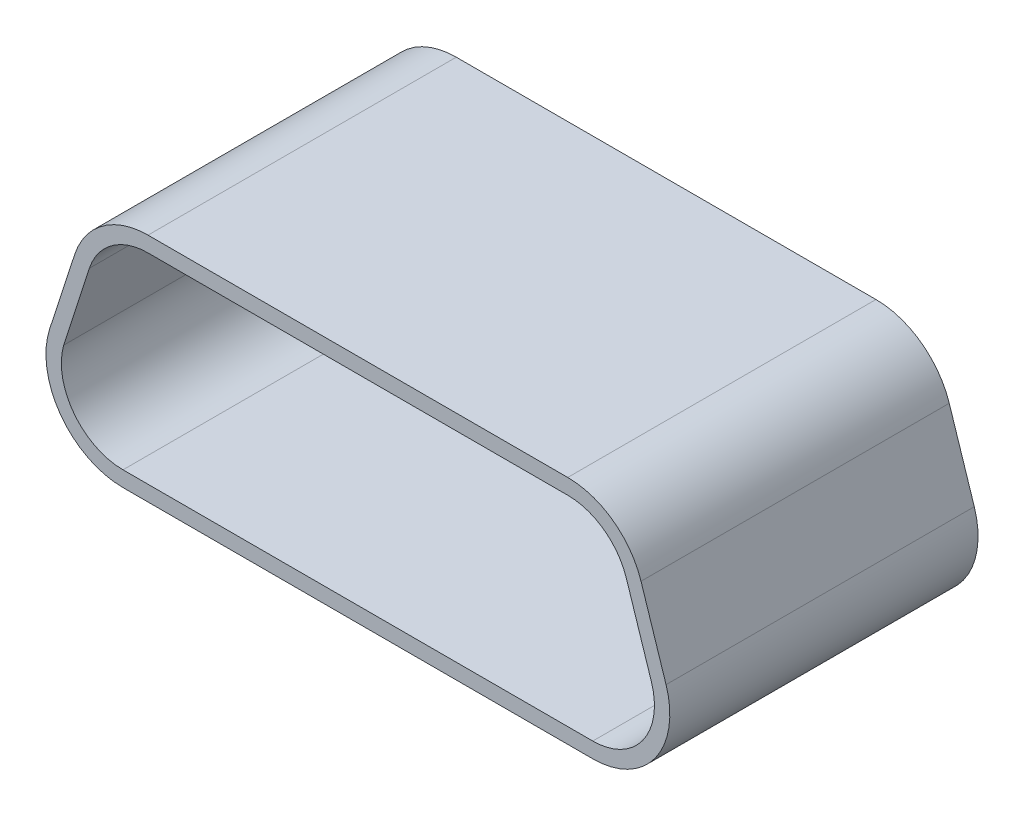
SolidWorks part; units mm, degrees
ref_plane "Płaszczyzna przednia" through (0, 0, 0) normal (0, 0, 1) x (1, 0, 0)
ref_plane "Płaszczyzna górna" through (0, 0, 0) normal (0, 1, 0) x (1, 0, 0)
ref_plane "Płaszczyzna prawa" through (0, 0, 0) normal (1, 0, 0) x (0, 0, -1)
sketch "Szkic1" plane through (0, 0, 0) normal (0, 0, 1) x (1, 0, 0)
  line L0 (-7.521, 0) -> (36.7255, 0)
  line L1 (36.7255, 0) -> (35.1009, 5)
  line L2 (-5.8964, 5) -> (35.1009, 5) construction
  line L3 (-2.6472, 15) -> (31.8517, 15)
  line L4 (-5.8964, 5) -> (-7.521, 0)
  line L5 (-5.8964, 5) -> (-2.6472, 15)
  line L6 (31.8517, 15) -> (35.1009, 5)
extrude "Dodanie-wyciągnięcie1" add sketch "Szkic1" along normal blind 20
fillet "Zaokrąglenie2" radius 5 4 edges at (-2.6472, 15, 10) (-7.521, 0, 10) (31.8517, 15, 10) (36.7255, 0, 10)
sketch "Szkic2" plane through (0, 0, 20) normal (0, 0, 1) x (1, 0, 0)
  line L2 (0.9855, 14) -> (28.219, 14)
  line L3 (28.219, 15) -> (0.9855, 15) construction
  line L5 (-0.6391, 1) -> (29.8436, 1)
  line L7 (33.6479, 6.2361) -> (32.0233, 11.2361)
  line L8 (-2.8188, 11.2361) -> (-4.4919, 6.0753)
  arc A4 (-4.4919, 6.0753) -> (-0.6391, 1) centre (-0.6391, 5) ccw
  arc A5 (0.9855, 14) -> (-2.8204, 11.2311) centre (0.9855, 10) ccw
  arc A6 (32.0233, 11.2361) -> (28.219, 14) centre (28.219, 10) ccw
  arc A7 (29.8436, 1) -> (33.6479, 6.2361) centre (29.8436, 5) ccw
  dimension "D2" = 1
extrude "Wytnij-wyciągnięcie1" cut sketch "Szkic2" against normal through all contours L5 A7 L7 A6 L2 A5 L8 A4
ref_plane "Płaszczyzna1" through (14.6023, 15, 0) normal (1, 0, 0) x (0, 0, -1)
sketch "Szkic3" plane through (0, 0, 0) normal (0, 0, -1) x (-1, 0, 0)
  line L0 (-14.6023, 14) -> (-14.6023, 1) construction
  line L1 (-0.9855, 14) -> (-28.219, 14) construction
  line L2 (0.6391, 1) -> (-29.8436, 1) construction
  line L3 (-0.9855, 14) -> (-0.9855, 1) construction
  line L5 (-0.9855, 7.5) -> (-14.6023, 7.5) construction
ref_plane "Płaszczyzna2" through (0, 7.5, 0) normal (0, 1, 0) x (1, 0, 0)
